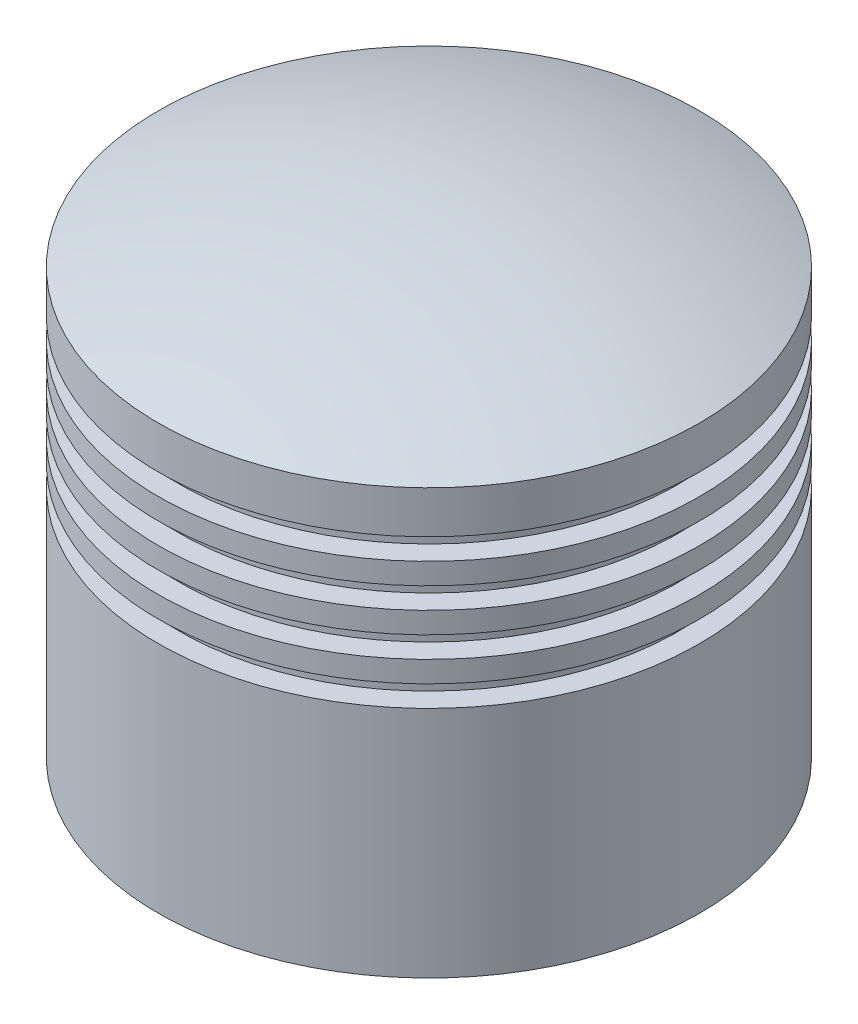
SolidWorks part; units mm, degrees
ref_plane "Front Plane" through (0, 0, 0) normal (0, 0, 1) x (1, 0, 0)
ref_plane "Top Plane" through (0, 0, 0) normal (0, 1, 0) x (1, 0, 0)
ref_plane "Right Plane" through (0, 0, 0) normal (1, 0, 0) x (0, 0, -1)
sketch "Sketch1" plane through (0, 0, 0) normal (0, 0, 1) x (1, 0, 0)
  line L0 (0, 0) -> (50000, 0) construction
  line L1 (0, 0) -> (0, 50000) construction
  line L2 (63.7223, 0) -> (63.7223, 55)
  line L3 (63.7223, 55) -> (58.7223, 55)
  line L4 (58.7223, 55) -> (58.7223, 60)
  line L5 (58.7223, 60) -> (63.7223, 60)
  line L6 (63.7223, 60) -> (63.7223, 65)
  line L7 (63.7223, 65) -> (58.7223, 65)
  line L8 (58.7223, 65) -> (58.7223, 70)
  line L9 (58.7223, 70) -> (63.7223, 70)
  line L10 (63.7223, 70) -> (63.7223, 75)
  line L11 (63.7223, 75) -> (58.7223, 75)
  line L12 (58.7223, 75) -> (58.7223, 80)
  line L13 (58.7223, 80) -> (63.7223, 80)
  line L14 (63.7223, 80) -> (63.7223, 85)
  line L15 (63.7223, 85) -> (58.7223, 85)
  line L16 (58.7223, 85) -> (58.7223, 90)
  line L17 (58.7223, 90) -> (63.7223, 90)
  line L18 (63.7223, 90) -> (63.7223, 100)
  line L19 (63.7223, 0) -> (50, 0)
  line L20 (50, 0) -> (50, 30)
  line L21 (50, 30) -> (43, 30)
  line L22 (43, 30) -> (43, 99.6205)
  line L23 (0, 112.3946) -> (0, 105.3946)
  arc A0 (43, 99.6205) -> (0, 105.3946) centre (0, -57.6054) ccw
  arc A1 (63.7223, 100) -> (0, 112.3946) centre (0, -57.6054) ccw
  dimension "D9" = 170
  dimension "D10" = 163
  dimension "D1" = 13.7223
  dimension "D2" = 86
  dimension "D3" = 5
  dimension "D4" = 30
  dimension "D5" = 90
  dimension "D6" = 100
  dimension "D7" = 7
  dimension "D8" = 5
revolve "Revolve1" add sketch "Sketch1" angle 360 about L1
